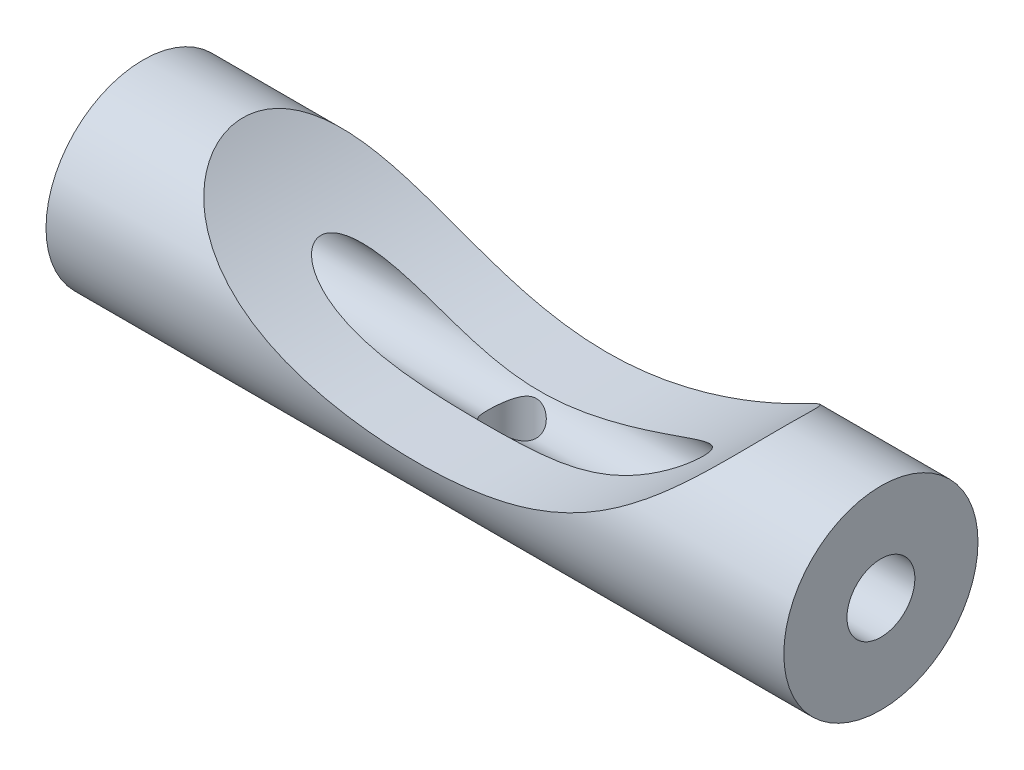
SolidWorks part; units mm, degrees
ref_plane "Front Plane" through (0, 0, 0) normal (0, 0, 1) x (1, 0, 0)
ref_plane "Top Plane" through (0, 0, 0) normal (0, 1, 0) x (1, 0, 0)
ref_plane "Right Plane" through (0, 0, 0) normal (1, 0, 0) x (0, 0, -1)
sketch "Sketch1" plane through (0, 0, 0) normal (1, 0, 0) x (0, 0, -1)
  circle A0 centre (0, 0) radius 5
  dimension "D1" = 10
extrude "Boss-Extrude1" add sketch "Sketch1" along normal mid plane 38
sketch "Sketch2" plane through (0, 0, 0) normal (0, 0, 1) x (1, 0, 0)
  line L0 (19, 5) -> (-19, 5) construction
  line L1 (0, -1) -> (0, 18) construction
  line L3 (-19, -5) -> (19, -5) construction
  arc A0 (-13.8564, 5) -> (13.8564, 5) centre (0, 18) ccw
  dimension "D1" = 19
  dimension "D2" = 4
extrude "Cut-Extrude1" cut sketch "Sketch2" against normal through all and the other way through all
sketch "Sketch3" plane through (0, 0, 0) normal (1, 0, 0) x (0, 0, -1)
  circle A0 centre (0, 0) radius 1.75
  dimension "D1" = 3.5
extrude "Cut-Extrude2" cut sketch "Sketch3" against normal mid plane 40
sketch "Sketch4" plane through (0, 0, 0) normal (0, 1, 0) x (1, 0, 0)
  circle A0 centre (0, 0) radius 1.25
  dimension "D1" = 2.5
extrude "Cut-Extrude3" cut sketch "Sketch4" against normal through all
